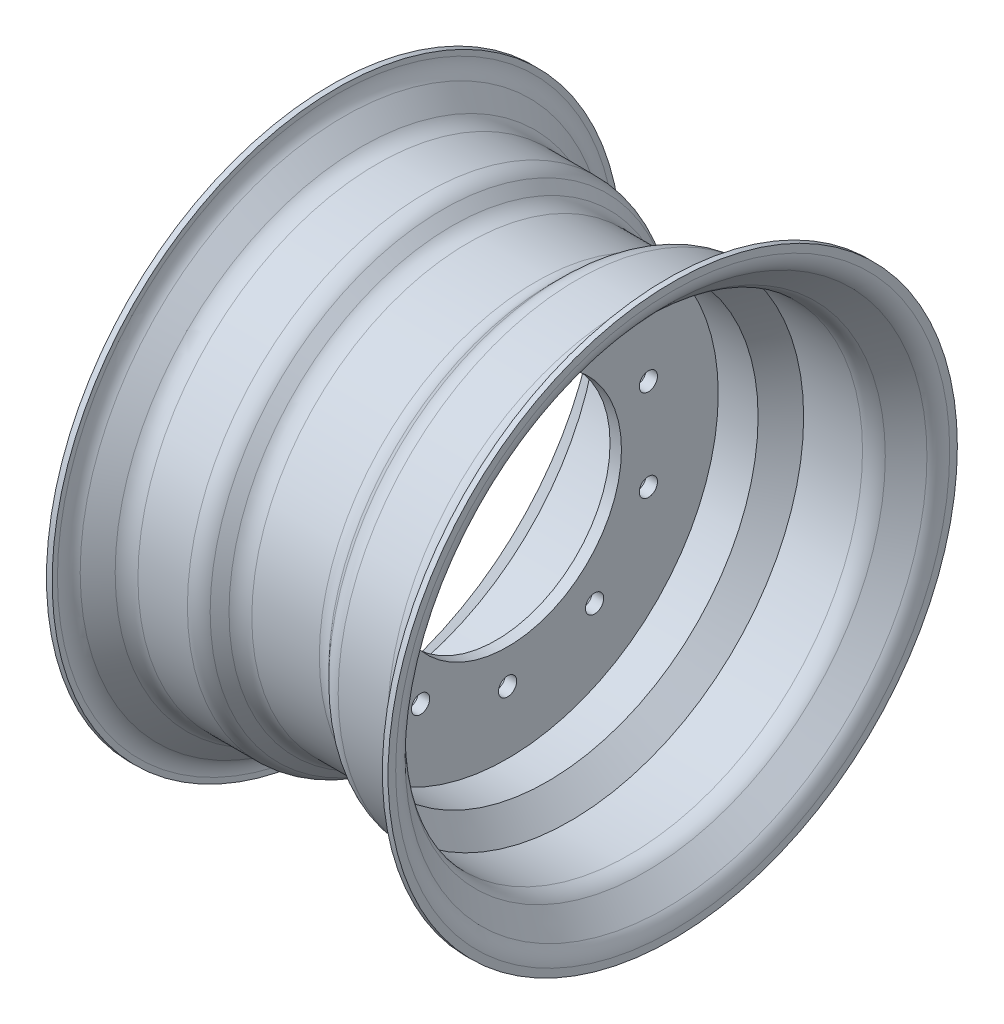
SolidWorks part; units mm, degrees
ref_plane "Front Plane" through (0, 0, 0) normal (0, 0, 1) x (1, 0, 0)
ref_plane "Top Plane" through (0, 0, 0) normal (0, 1, 0) x (1, 0, 0)
ref_plane "Right Plane" through (0, 0, 0) normal (1, 0, 0) x (0, 0, -1)
sketch "Sketch1" plane through (0, 0, 0) normal (0, 0, 1) x (1, 0, 0)
  line L0 (0, 166.5468) -> (0, 0) construction
  line L1 (0, 0) -> (-231.6547, 0) construction
  line L2 (-150, 250) -> (-150, 235)
  line L3 (-150, 235) -> (-120, 205)
  line L4 (-120, 205) -> (-60, 205)
  line L5 (-60, 205) -> (-40, 185)
  line L6 (-40, 185) -> (-5, 185)
  line L7 (60, 205) -> (40, 185)
  line L8 (120, 205) -> (60, 205)
  line L9 (150, 235) -> (120, 205)
  line L10 (150, 250) -> (150, 235)
  line L11 (-145, 250) -> (-145, 237.0711)
  line L12 (-145, 237.0711) -> (-117.9289, 210)
  line L13 (-117.9289, 210) -> (-57.9289, 210)
  line L14 (-57.9289, 210) -> (-37.9289, 190)
  line L15 (-37.9289, 190) -> (37.9289, 190)
  line L16 (57.9289, 210) -> (37.9289, 190)
  line L17 (117.9289, 210) -> (57.9289, 210)
  line L18 (145, 237.0711) -> (117.9289, 210)
  line L19 (145, 250) -> (145, 237.0711)
  line L20 (-150, 250) -> (-145, 250)
  line L21 (145, 250) -> (150, 250)
  line L22 (5, 185) -> (40, 185)
  line L24 (-5, 185) -> (-5, 100)
  line L25 (-5, 100) -> (5, 100)
  line L26 (5, 185) -> (5, 100)
  line L27 (-5, 185) -> (5, 100) construction
  line L28 (-5, 100) -> (5, 185) construction
  line L29 (-40, 185) -> (40, 185) construction
  point P11 (0, 185)
  point P25 (0, 142.5)
  dimension "D1" = 250
  dimension "D2" = 15
  dimension "D3" = 30
  dimension "D4" = 60
  dimension "D5" = 20
  dimension "D6" = 40
  dimension "D7" = 135
  dimension "D8" = 5
  dimension "D9" = 10
  dimension "D10" = 100
revolve "Revolve1" add sketch "Sketch1" angle 360 about L1
fillet "Fillet1" radius 20 9 edges at (120, 0, -205) (150, 0, -235) (-145, 0, -237.0711) (117.9289, 0, -210) (57.9289, 0, -210) (37.9289, 0, -190) (-37.9289, 0, -190) (-57.9289, 0, -210) (-117.9289, 0, -210)
sketch "Sketch2" plane through (5, 0, 0) normal (1, 0, 0) x (0, 0, -1)
  circle A0 centre (0, 130) radius 8
  point P2 (0, 0)
  dimension "D2" = 16
  dimension "D1" = 130
extrude "Cut-Extrude1" cut sketch "Sketch2" against normal blind 10
pattern_circular "CirPattern1" count 10 over 360 about axis through (0, 0, 0) along (1, 0, 0) of "Cut-Extrude1"
